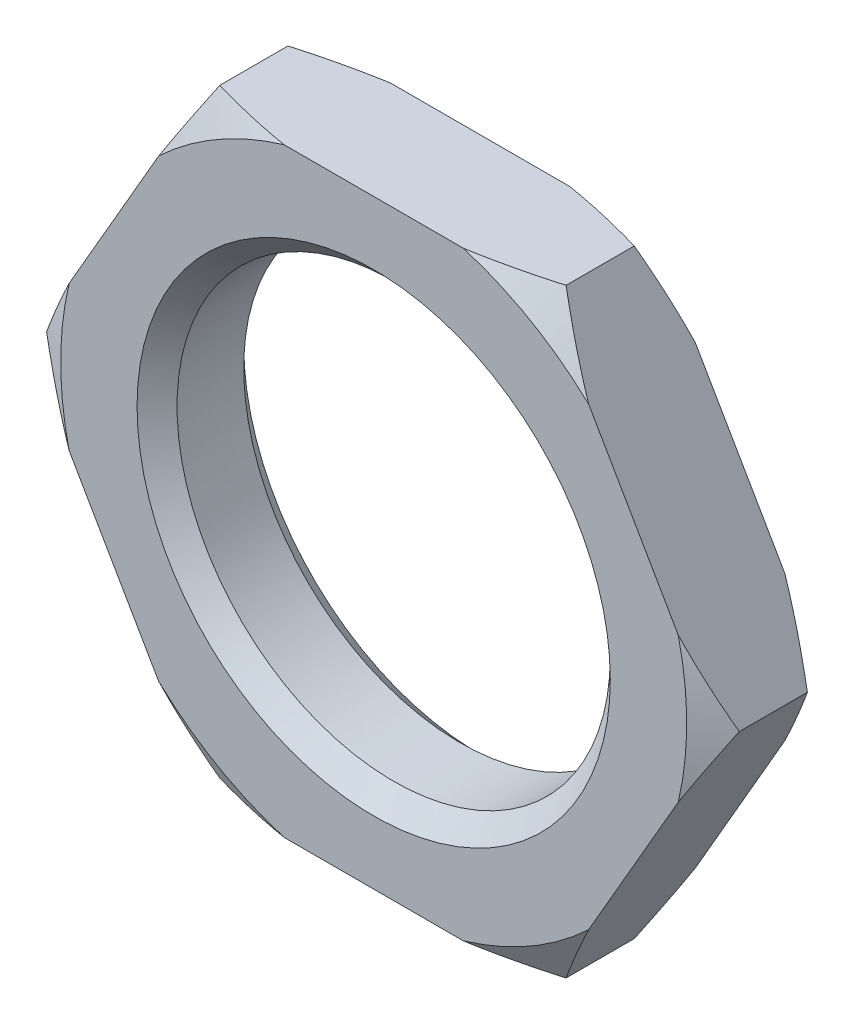
SolidWorks part; units mm, degrees
material "Acier allié inoxydable"
ref_plane "Plan de face" through (0, 0, 0) normal (0, 0, 1) x (1, 0, 0)
ref_plane "Plan de dessus" through (0, 0, 0) normal (0, 1, 0) x (1, 0, 0)
ref_plane "Plan de droite" through (0, 0, 0) normal (1, 0, 0) x (0, 0, -1)
sketch "Esquisse1" plane through (0, 0, 0) normal (0, 0, 1) x (1, 0, 0)
  line L1 (5.1962, 0) -> (2.5981, 4.5)
  line L2 (2.5981, 4.5) -> (-2.5981, 4.5)
  line L3 (-2.5981, 4.5) -> (-5.1962, 0)
  line L4 (-5.1962, 0) -> (-2.5981, -4.5)
  line L5 (-2.5981, -4.5) -> (2.5981, -4.5)
  line L6 (2.5981, -4.5) -> (5.1962, 0)
  circle A0 centre (0, 0) radius 4.5 construction
  circle A1 centre (0, 0) radius 3.25
  dimension "D2" = 6.5
  dimension "D1" = 9
extrude "Boss.-Extru.1" add sketch "Esquisse1" along normal blind 1.6
sketch "Esquisse2" plane through (0, 0, 0) normal (0, 1, 0) x (1, 0, 0)
  line L0 (-4.6962, 0) -> (-5.1962, -0.2887)
  line L1 (-5.1962, -0.2887) -> (-5.1962, -1.3113)
  line L2 (-5.1962, -1.3113) -> (-4.6962, -1.6)
  line L3 (-4.6962, -1.6) -> (-6.1962, -1.6)
  line L4 (-6.1962, -1.6) -> (-6.1962, 0)
  line L5 (-6.1962, 0) -> (-4.6962, 0)
  line L6 (-5.1962, -1.6) -> (-5.1962, 0) construction
  line L8 (-2.5981, 0) -> (-5.1962, 0) construction
  line L9 (-2.5981, -1.6) -> (-5.1962, -1.6) construction
  line L10 (-4.6962, 0) -> (-4.6962, -1.6) construction
  line L11 (0, 0) -> (0, -1.6) construction
  line L12 (2.5981, -1.6) -> (-2.5981, -1.6) construction
  dimension "D1" = 30
  dimension "D2" = 30
  dimension "D3" = 1
  dimension "D4" = 0.5
revolve "Enlèvement de matière-Révolution1" cut sketch "Esquisse2" angle 360 about L11
chamfer "Chanfrein1" distance 0.3 angle 45 2 edges at (3.25, 0, 1.6) (3.25, 0, 0)
